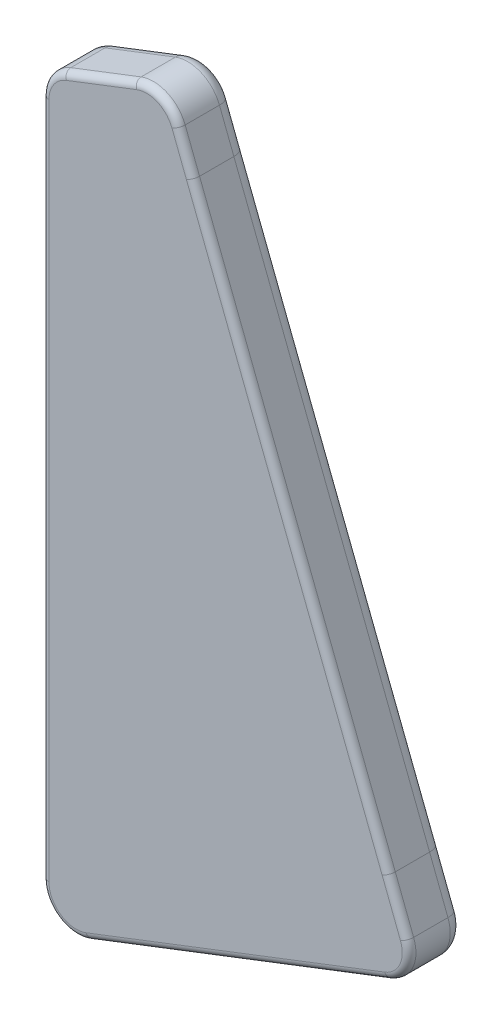
SolidWorks part; units mm, degrees
ref_plane "Front Plane" through (0, 0, 0) normal (0, 0, 1) x (1, 0, 0)
ref_plane "Top Plane" through (0, 0, 0) normal (0, 1, 0) x (1, 0, 0)
ref_plane "Right Plane" through (0, 0, 0) normal (1, 0, 0) x (0, 0, -1)
sketch "Sketch1" plane through (0, 0, 0) normal (0, 0, 1) x (1, 0, 0)
  line L0 (18.4762, 253.8079) -> (21.8106, 245.1666) construction
  line L1 (0.1788, 248.4083) -> (16.4729, 254.6956) construction
  line L2 (-0.8128, 243.84) -> (-0.8128, 246.9628) construction
  line L3 (-0.8128, 238.76) -> (-0.8128, 243.84) construction
  line L4 (-0.8128, 99.06) -> (-0.8128, 238.76) construction
  line L5 (-0.8128, 93.98) -> (-0.8128, 99.06) construction
  line L6 (-0.8128, 90.0082) -> (-0.8128, 93.98) construction
  line L7 (4.9999, 89.9925) -> (1.2944, 88.5627) construction
  line L8 (9.7393, 91.8213) -> (4.9999, 89.9925) construction
  line L9 (61.8728, 111.9379) -> (9.7393, 91.8213) construction
  line L10 (66.6122, 113.7667) -> (61.8728, 111.9379) construction
  line L11 (70.514, 115.2723) -> (66.6122, 113.7667) construction
  line L12 (67.153, 128.2866) -> (71.4018, 117.2756) construction
  line L13 (18.4762, 253.8079) -> (21.8106, 245.1666)
  line L14 (0.1788, 248.4083) -> (16.4729, 254.6956)
  line L15 (-0.8128, 243.84) -> (-0.8128, 246.9628)
  line L16 (-0.8128, 238.76) -> (-0.8128, 243.84)
  line L17 (-0.8128, 99.06) -> (-0.8128, 238.76)
  line L18 (-0.8128, 93.98) -> (-0.8128, 99.06)
  line L19 (-0.8128, 90.0082) -> (-0.8128, 93.98)
  line L20 (4.9999, 89.9925) -> (1.2944, 88.5627)
  line L21 (9.7393, 91.8213) -> (4.9999, 89.9925)
  line L22 (61.8728, 111.9379) -> (9.7393, 91.8213)
  line L23 (66.6122, 113.7667) -> (61.8728, 111.9379)
  line L24 (70.514, 115.2723) -> (66.6122, 113.7667)
  line L25 (67.153, 128.2866) -> (71.4018, 117.2756)
  line L26 (67.153, 128.2866) -> (21.8106, 245.1666)
  line L27 (73.0752, 130.5779) -> (27.7328, 247.4579)
  line L28 (24.4004, 256.0939) -> (27.7328, 247.4579)
  line L29 (-2.1072, 254.3325) -> (14.1869, 260.6199)
  line L30 (-7.1628, 243.84) -> (-7.1628, 246.9628)
  line L31 (-7.1628, 238.76) -> (-7.1628, 243.84)
  line L32 (-7.1628, 99.06) -> (-7.1628, 238.76)
  line L33 (-7.1628, 93.98) -> (-7.1628, 99.06)
  line L34 (-7.1628, 90.0082) -> (-7.1628, 93.98)
  line L35 (7.2859, 84.0682) -> (3.5804, 82.6384)
  line L36 (12.0253, 85.897) -> (7.2859, 84.0682)
  line L37 (64.1587, 106.0137) -> (12.0253, 85.897)
  line L38 (68.8981, 107.8424) -> (64.1587, 106.0137)
  line L39 (72.8, 109.348) -> (68.8981, 107.8424)
  line L40 (73.0752, 130.5779) -> (77.326, 119.5616)
  arc A0 (18.4762, 253.8079) -> (16.4729, 254.6956) centre (17.0307, 253.2501) ccw construction
  arc A1 (0.1788, 248.4083) -> (-0.8128, 246.9628) centre (0.7366, 246.9628) ccw construction
  arc A2 (-0.8128, 90.0082) -> (1.2944, 88.5627) centre (0.7366, 90.0082) ccw construction
  arc A3 (70.514, 115.2723) -> (71.4018, 117.2756) centre (69.9563, 116.7178) ccw construction
  arc A4 (18.4762, 253.8079) -> (16.4729, 254.6956) centre (17.0307, 253.2501) ccw
  arc A5 (0.1788, 248.4083) -> (-0.8128, 246.9628) centre (0.7366, 246.9628) ccw
  arc A6 (-0.8128, 90.0082) -> (1.2944, 88.5627) centre (0.7366, 90.0082) ccw
  arc A7 (70.514, 115.2723) -> (71.4018, 117.2756) centre (69.9563, 116.7178) ccw
  arc A8 (24.4004, 256.0939) -> (14.1869, 260.6199) centre (17.0307, 253.2501) ccw
  arc A9 (-2.1072, 254.3325) -> (-7.1628, 246.9628) centre (0.7366, 246.9628) ccw
  arc A10 (-7.1628, 90.0082) -> (3.5804, 82.6384) centre (0.7366, 90.0082) ccw
  arc A11 (72.8, 109.348) -> (77.326, 119.5616) centre (69.9563, 116.7178) ccw
  dimension "D1" = 6.35
extrude "Boss-Extrude1" add sketch "Sketch1" along normal blind 12.7 contours L32 L31 L30 A9 L29 A8 L28 L27 L40 A11 L39 L38 L37 L36 L35 A10 L34 L33
fillet "Fillet1" radius 3.175 10 edges at (20.231, 260.4722, 0) (26.0666, 251.7759, 0) (50.404, 189.0179, 0) (75.2006, 125.0697, 0) (77.1783, 113.5174, 0) (38.1902, 95.9932, 0) (-3.732, 83.4942, 0) (-7.1628, 168.4855, 0) (-5.7774, 251.4313, 0) (6.0399, 257.4762, 0)
fillet "Fillet2" radius 1.5875 10 edges at (-3.732, 83.4942, 12.7) (38.1902, 95.9932, 12.7) (77.1783, 113.5174, 12.7) (75.2006, 125.0697, 12.7) (50.404, 189.0179, 12.7) (26.0666, 251.7759, 12.7) (20.231, 260.4722, 12.7) (6.0399, 257.4762, 12.7) (-5.7774, 251.4313, 12.7) (-7.1628, 168.4855, 12.7)
sketch "Sketch3" plane through (0, 0, 0) normal (0, 0, -1) x (-1, 0, 0)
  line L0 (-10.5791, 113.919) -> (-10.5791, 127.381) construction
  line L1 (0, 243.84) -> (0.8128, 243.84)
  line L2 (0, 243.84) -> (0, 93.98)
  line L3 (0, 93.98) -> (0.8128, 93.98)
  line L4 (0.8128, 243.84) -> (0.8128, 93.98)
extrude "Cut-Extrude1" cut sketch "Sketch3" against normal blind 6.35
sketch "Sketch4" plane through (0, 0, 0) normal (0, 0, -1) x (-1, 0, 0)
  line L0 (-71.657, 112.3102) -> (-2.4374, 85.6005) construction
  line L1 (-66.3196, 114.525) -> (-4.7073, 90.7508)
  line L2 (-66.3196, 114.525) -> (-66.6122, 113.7667)
  line L3 (-66.6122, 113.7667) -> (-4.9999, 89.9925)
  line L4 (-4.7073, 90.7508) -> (-4.9999, 89.9925)
  line L5 (-4.9999, 89.9925) -> (-9.7393, 91.8213) construction
extrude "Cut-Extrude2" cut sketch "Sketch4" against normal blind 6.35
